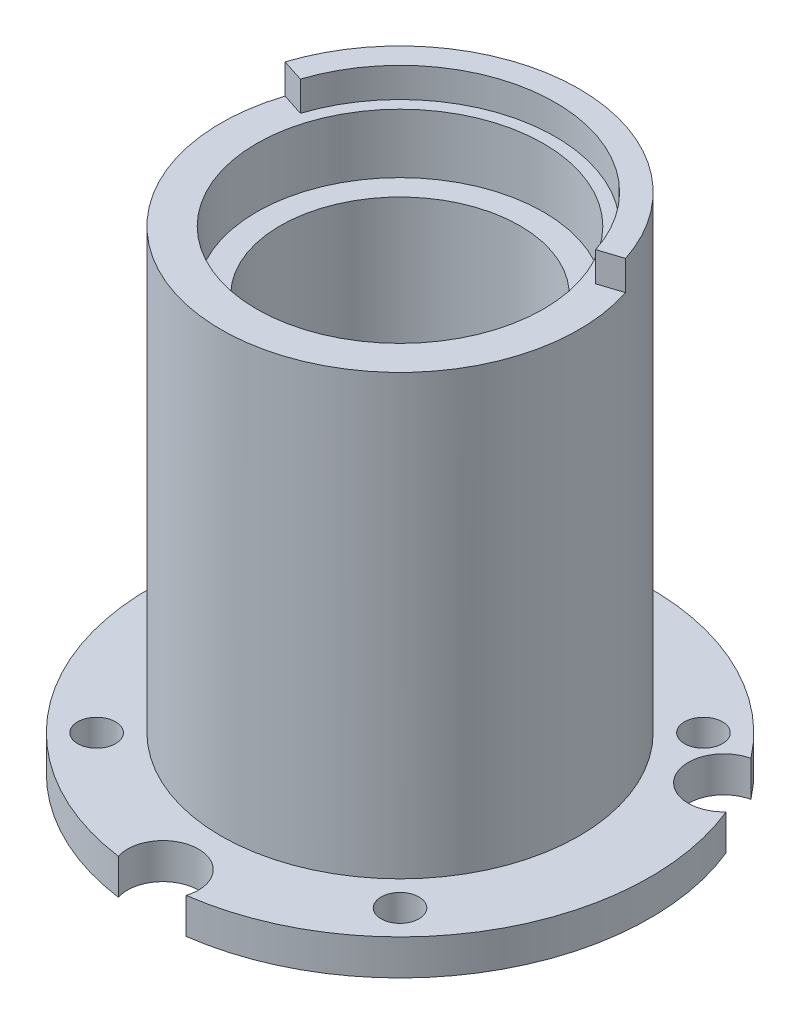
SolidWorks part; units mm, degrees
ref_plane "前视基准面" through (0, 0, 0) normal (0, 0, 1) x (1, 0, 0)
ref_plane "上视基准面" through (0, 0, 0) normal (0, 1, 0) x (1, 0, 0)
ref_plane "右视基准面" through (0, 0, 0) normal (1, 0, 0) x (0, 0, -1)
sketch "草图1" plane through (0, 0, 0) normal (0, 0, 1) x (1, 0, 0)
  line L0 (0, 0) -> (0, 38.7327) construction
  line L1 (12.1, -0.3434) -> (12.1, 4.6566)
  line L2 (12.1, 4.6566) -> (10.1, 4.6566)
  line L3 (10.1, 4.6566) -> (10.1, 34.6566)
  line L4 (10.1, 34.6566) -> (12.1, 34.6566)
  line L5 (12.1, 34.6566) -> (12.1, 39.6566)
  line L6 (12.1, 39.6566) -> (15.1, 39.6566)
  line L7 (15.1, 39.6566) -> (15.1, -0.3434)
  line L8 (15.1, -0.3434) -> (12.1, -0.3434)
  dimension "D1" = 5
  dimension "D2" = 2
  dimension "D3" = 3
  dimension "D4" = 5
  dimension "D5" = 5
  dimension "D6" = 2
  dimension "D7" = 30
  dimension "D8" = 12.1
revolve "旋转1" add sketch "草图1" angle 360 about L0
sketch "草图2" plane through (0, -0.3434, 0) normal (0, -1, 0) x (1, 0, 0)
  line L1 (12.7986, 12.7986) -> (-12.7986, 12.7986) construction
  line L2 (12.7986, 12.7986) -> (12.7986, -12.7986) construction
  line L3 (12.7986, -12.7986) -> (-12.7986, -12.7986) construction
  line L4 (-12.7986, 12.7986) -> (-12.7986, -12.7986) construction
  line L5 (12.7986, 12.7986) -> (-12.7986, -12.7986) construction
  line L6 (12.7986, -12.7986) -> (-12.7986, 12.7986) construction
  circle A0 centre (0, 0) radius 15.1 construction
  circle A1 centre (0, 0) radius 15.1
  circle A2 centre (0, 0) radius 21.1
  circle A3 centre (0, 0) radius 18.1 construction
  circle A4 centre (-12.7986, 12.7986) radius 1.6
  circle A5 centre (12.7986, 12.7986) radius 1.6
  circle A6 centre (12.7986, -12.7986) radius 1.6
  circle A7 centre (-12.7986, -12.7986) radius 1.6
  dimension "D1" = 6
  dimension "D2" = 3
  dimension "D4" = 3.2
  dimension "D5" = 3.2
  dimension "D6" = 3.2
  dimension "D7" = 3.2
  dimension "D3" = 90
extrude "凸台-拉伸1" add sketch "草图2" against normal blind 3
sketch "草图4" plane through (0, -0.3434, 0) normal (0, -1, 0) x (1, 0, 0)
  line L0 (0, 0) -> (0, 20) construction
  line L1 (0, 0) -> (17.3205, -10) construction
  line L2 (0, 0) -> (-17.3205, -10) construction
  circle A0 centre (0, 0) radius 20 construction
  circle A1 centre (0, 20) radius 3
  circle A2 centre (17.3205, -10) radius 3
  circle A3 centre (-17.3205, -10) radius 3
  dimension "D1" = 40
  dimension "D4" = 6
  dimension "D5" = 6
  dimension "D6" = 6
  dimension "D2" = 120
  dimension "D3" = 120
extrude "切除-拉伸1" cut sketch "草图4" against normal blind 3
sketch "草图5" plane through (0, 0, 0) normal (0, 0, 1) x (1, 0, 0)
  line L0 (-16.6744, -0.3434) -> (16.6744, -0.3434) construction
  circle A0 centre (0, 13.6566) radius 4
  dimension "D2" = 8
  dimension "D1" = 14
extrude "切除-拉伸2" cut sketch "草图5" against normal blind 42 contours A0
sketch "草图6" plane through (0, 39.6566, 0) normal (0, 1, 0) x (1, 0, 0)
  line L1 (12.4588, 4.0481) -> (14.361, 4.6662)
  line L2 (-12.4588, 4.0481) -> (-14.361, 4.6662)
  circle A0 centre (0, 0) radius 15.1 construction
  arc A1 (14.361, 4.6662) -> (-14.361, 4.6662) centre (0, 0) ccw
  circle A2 centre (0, 0) radius 12.1 construction
  arc A4 (12.4588, 4.0481) -> (-12.4588, 4.0481) centre (0, 0) ccw
  dimension "D1" = 1
extrude "凸台-拉伸4" add sketch "草图6" along normal blind 2.5 contours A4 L2 A1 L1
